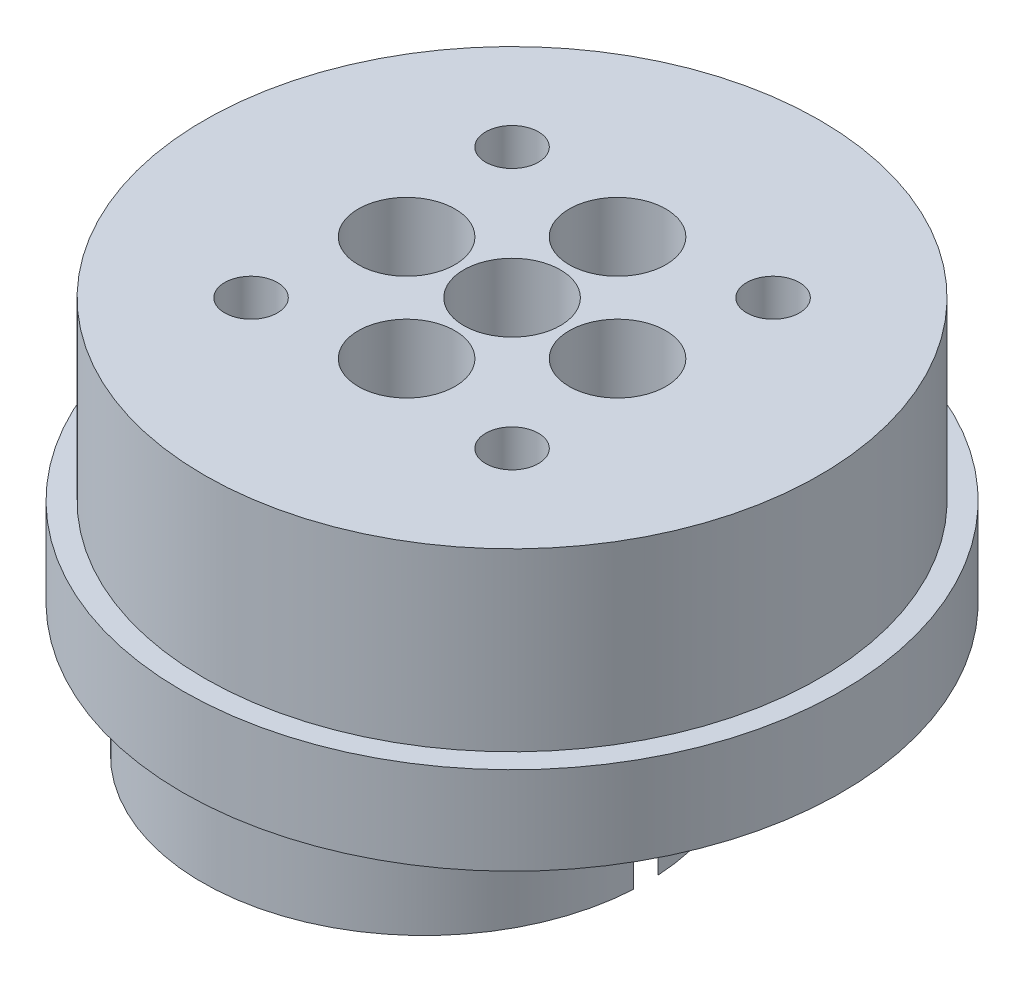
SolidWorks part; units mm, degrees
ref_plane "Front Plane" through (0, 0, 0) normal (0, 0, 1) x (1, 0, 0)
ref_plane "Top Plane" through (0, 0, 0) normal (0, 1, 0) x (1, 0, 0)
ref_plane "Right Plane" through (0, 0, 0) normal (1, 0, 0) x (0, 0, -1)
sketch "Sketch1" plane through (0, 0, 0) normal (0, 1, 0) x (1, 0, 0)
  circle A0 centre (0, 0) radius 15
  dimension "D1" = 30
extrude "Boss-Extrude1" add sketch "Sketch1" along normal blind 5 contours A0
sketch "Sketch2" plane through (0, 5, 0) normal (0, 1, 0) x (1, 0, 0)
  line L0 (5, 0) -> (0, 0) construction
  circle A0 centre (5, 0) radius 12.6
  dimension "D2" = 25.2
  dimension "D1" = 5
extrude "Boss-Extrude2" add sketch "Sketch2" along normal blind 10
sketch "Sketch3" plane through (0, 15, 0) normal (0, 1, 0) x (1, 0, 0)
  circle A0 centre (0, 0) radius 7.5
  dimension "D1" = 15
extrude "Boss-Extrude3" add sketch "Sketch3" along normal blind 5
sketch "Sketch4" plane through (0, 20, 0) normal (0, 1, 0) x (1, 0, 0)
  line L0 (-5, 0) -> (0, 0) construction
  circle A0 centre (-5, 0) radius 12.625
  dimension "D2" = 25.25
  dimension "D1" = 5
extrude "Boss-Extrude4" add sketch "Sketch4" along normal blind 10
sketch "Sketch8" plane through (0, 30, 0) normal (0, 1, 0) x (1, 0, 0)
  circle A0 centre (0, 0) radius 18.75
  dimension "D1" = 37.5
extrude "Boss-Extrude5" add sketch "Sketch8" along normal blind 5
sketch "Sketch10" plane through (0, 35, 0) normal (0, 1, 0) x (1, 0, 0)
  circle A0 centre (0, 0) radius 17.5
  dimension "D1" = 35
extrude "Boss-Extrude7" add sketch "Sketch10" along normal blind 10
sketch "Sketch11" plane through (0, 0, 0) normal (0, -1, 0) x (1, 0, 0)
  circle A0 centre (0, 0) radius 17.65
  dimension "D1" = 35.3
extrude "Boss-Extrude8" add sketch "Sketch11" along normal blind 10
sketch "Sketch12" plane through (0, -10, 0) normal (0, -1, 0) x (1, 0, 0)
  circle A1 centre (0, 0) radius 6 construction
  circle A2 centre (0, 6) radius 1.75
  circle A4 centre (0, -6) radius 1.75
  circle A7 centre (6, 0) radius 1.75
  circle A8 centre (-6, 0) radius 1.75
  circle A9 centre (0, 0) radius 2.75
  dimension "D1" = 3.5
  dimension "D2" = 12
  dimension "D3" = 5.5
extrude "Cut-Extrude1" cut sketch "Sketch12" against normal up to surface (55 mm away) up to face at (0, 45, 17.5)
sketch "Sketch27" plane through (0, 0, 0) normal (1, 0, 0) x (0, 0, -1)
  line L0 (-20.0285, 20) -> (19.9759, 20)
  line L1 (19.9759, 20) -> (19.9759, -10)
  line L2 (19.9759, -10) -> (-20.0285, -10)
  line L3 (-20.0285, -10) -> (-20.0285, 20)
  line L8 (-17.65, -10) -> (17.65, -10) construction
  line L12 (-12.625, 20) -> (12.625, 20) construction
extrude "Cut-Extrude12" cut sketch "Sketch27" against normal through all both and the other way through all
sketch "Sketch28" [suppressed] plane through (0, 30.5, 0) normal (0, -1, 0) x (1, 0, 0)
  circle A1 centre (0, 0) radius 2.75 construction
  circle A3 centre (0, 0) radius 2.75
  circle A23 centre (0, -10.5) radius 1.75 construction
  circle A25 centre (0, 10.5) radius 1.75 construction
  circle A27 centre (0, -10.5) radius 1.75
  circle A29 centre (0, 10.5) radius 1.75
sketch "Sketch29" [suppressed] plane through (0, 0, 0) normal (0, 1, 0) x (1, 0, 0)
  circle A0 centre (0, 0) radius 10
  circle A1 centre (0, 0) radius 6 construction
  circle A2 centre (0, 6) radius 1.75
  circle A3 centre (6, 0) radius 1.75
  circle A4 centre (0, 0) radius 2.75
  circle A5 centre (0, -6) radius 1.75
  circle A6 centre (-6, 0) radius 1.75
  dimension "D1" = 20
  dimension "D2" = 3.5
  dimension "D3" = 12
  dimension "D4" = 5.5
extrude "Boss-Extrude10" [suppressed] add sketch "Sketch29" along normal blind 5
sketch "Sketch30" plane through (0, 30, 0) normal (0, -1, 0) x (1, 0, 0)
  circle A3 centre (-5, 0) radius 12.625 construction
  circle A13 centre (6, 0) radius 1.75 construction
  circle A23 centre (-5, 0) radius 13
  circle A24 centre (0, 6) radius 1.75 construction
  circle A25 centre (0, -6) radius 1.75 construction
  circle A26 centre (-6, 0) radius 1.75 construction
  circle A27 centre (0, -6) radius 1.75
  circle A28 centre (-6, 0) radius 1.75
  circle A29 centre (0, 6) radius 1.75
  circle A30 centre (6, 0) radius 1.75
  circle A31 centre (0, 0) radius 2.75 construction
  circle A32 centre (0, 0) radius 2.75
  dimension "D1" = 26
extrude "Boss-Extrude11" add sketch "Sketch30" along normal blind 2
sketch "Sketch31" plane through (0, 45, 0) normal (0, 1, 0) x (1, 0, 0)
  line L0 (0, 0) -> (-7.4246, 7.4246) construction
  line L1 (0, 0) -> (0, 10.5) construction
  circle A0 centre (0, 0) radius 10.5 construction
  circle A1 centre (-7.4246, 7.4246) radius 1.5
  circle A2 centre (7.4246, 7.4246) radius 1.5
  circle A3 centre (7.4246, -7.4246) radius 1.5
  circle A4 centre (-7.4246, -7.4246) radius 1.5
  point P15 (0, 0)
  dimension "D1" = 21
  dimension "D3" = 3
  dimension "D2" = 45
  dimension "D4" = 4
extrude "Cut-Extrude13" cut sketch "Sketch31" against normal blind 10
sketch "Sketch32" plane through (0, 45, 0) normal (0, 1, 0) x (1, 0, 0)
  circle A0 centre (-6, 0) radius 2.75
  circle A1 centre (0, 6) radius 2.75
  circle A2 centre (6, 0) radius 2.75
  circle A3 centre (0, -6) radius 2.75
  dimension "D1" = 5.5
extrude "Cut-Extrude14" cut sketch "Sketch32" against normal blind 4
